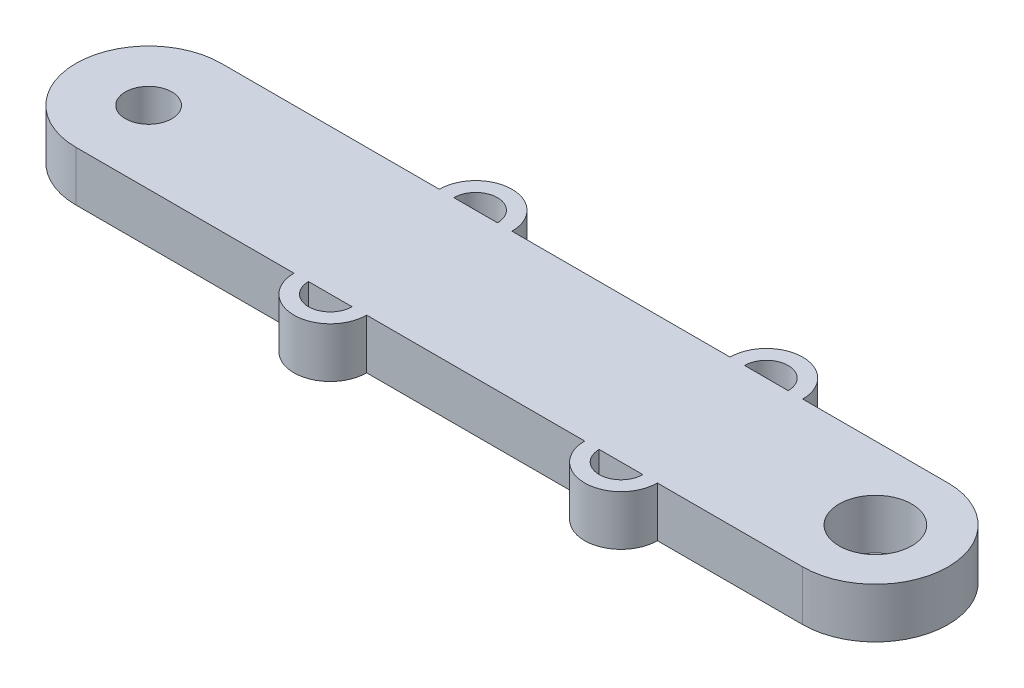
SolidWorks part; units mm, degrees
ref_plane "Alzado" through (0, 0, 0) normal (0, 0, 1) x (1, 0, 0)
ref_plane "Planta" through (0, 0, 0) normal (0, 1, 0) x (1, 0, 0)
ref_plane "Vista lateral" through (0, 0, 0) normal (1, 0, 0) x (0, 0, -1)
sketch "Croquis1" plane through (0, 0, 0) normal (0, 1, 0) x (1, 0, 0)
  line L7 (-50, -10) -> (50, -10)
  line L10 (-50, 10) -> (50, 10)
  line L11 (-50, 0) -> (50, 0) construction
  line L12 (-53.2, 0) -> (-53.2, 44.7716) construction
  line L13 (-60, 0) -> (-60, 44.7716) construction
  line L14 (-46.8, 0) -> (-46.8, 44.7716) construction
  arc A0 (50, 10) -> (50, -10) centre (50, 0) cw
  arc A1 (-50, -10) -> (-50, 10) centre (-50, 0) cw
  circle A3 centre (-50, 0) radius 3.2
  circle A8 centre (50, 0) radius 5
  dimension "D3" = 6.4
  dimension "D4" = 6.8
  dimension "D6" = 10
  dimension "D1" = 100
  dimension "D2" = 20
  dimension "D5" = 13.2
extrude "Saliente-Extruir2" add sketch "Croquis1" along normal blind 6.88 contours A1 L7 A0 L10 A3
sketch "Croquis3" plane through (0, 0, 0) normal (0, 1, 0) x (1, 0, 0)
  line L2 (-50, -10) -> (50, -10) construction
  line L3 (-20, -10) -> (-18, -10)
  line L4 (-20, -10) -> (-18, -10)
  line L5 (-12, -10) -> (-10, -10)
  line L6 (-50, 0) -> (-20, -10) construction
  line L7 (-12, -10) -> (-10, -10)
  arc A2 (-18, -10) -> (-12, -10) centre (-15, -10) ccw
  arc A3 (-20, -10) -> (-10, -10) centre (-15, -10) ccw
  dimension "D1" = 3
  dimension "D3" = 30
  dimension "D2" = 2
extrude "Saliente-Extruir3" add sketch "Croquis3" along normal up to surface (6.88 mm away) contours L3 A3 A2 up to face at (50, 6.88, 5)
pattern_linear "MatrizL1" count 2 spacing 40 along (1, 0, 0) of "Saliente-Extruir3"
mirror "Simetría1" about plane through (0, 0, 0) normal (0, 0, 1) of "MatrizL1", "Saliente-Extruir3"
